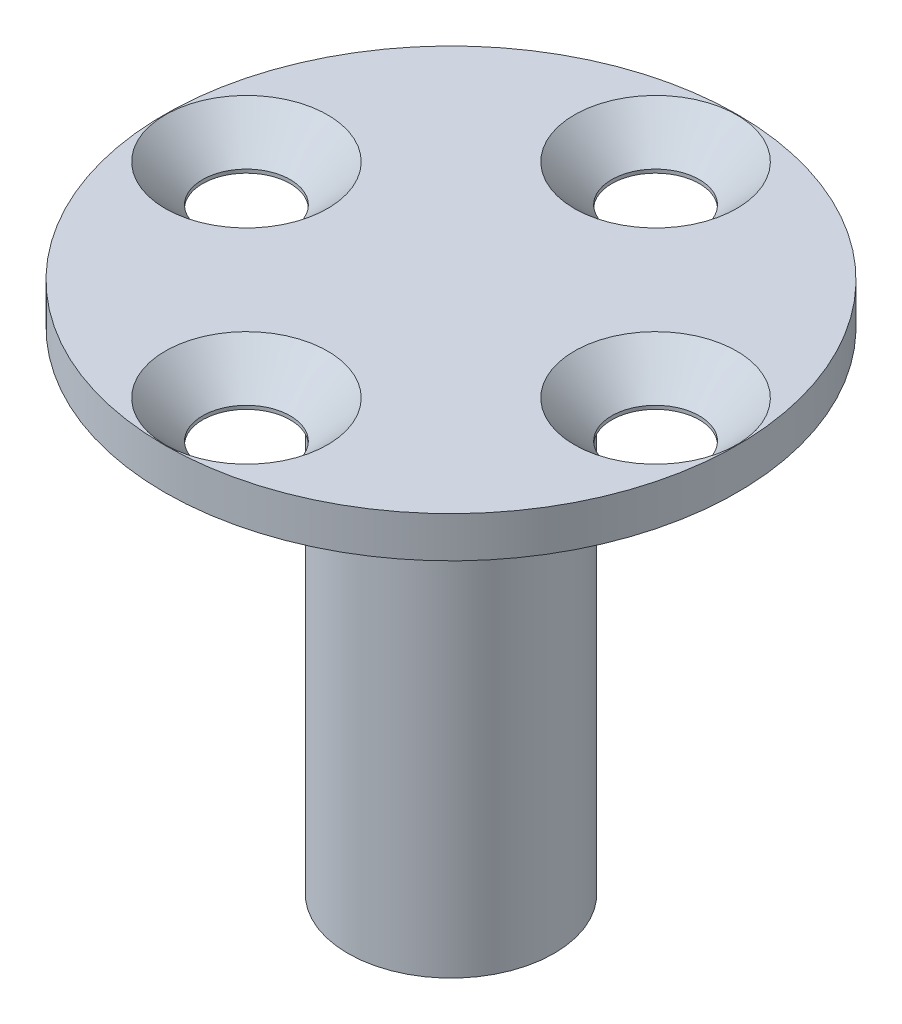
SolidWorks part; units mm, degrees
material "6061 Alloy"
ref_plane "Front" through (0, 0, 0) normal (0, 0, 1) x (1, 0, 0)
ref_plane "Top" through (0, 0, 0) normal (0, 1, 0) x (1, 0, 0)
ref_plane "Right" through (0, 0, 0) normal (1, 0, 0) x (0, 0, -1)
sketch "Sketch1" plane through (0, 0, 0) normal (0, 1, 0) x (1, 0, 0)
  circle A0 centre (0, 0) radius 4
  dimension "D1" = 8
extrude "Boss-Extrude1" add sketch "Sketch1" against normal blind 19.05
sketch "Sketch2" plane through (0, 0, 0) normal (0, 1, 0) x (1, 0, 0)
  circle A0 centre (0, 0) radius 11.1125
  dimension "D1" = 22.225
extrude "Boss-Extrude2" add sketch "Sketch2" along normal blind 3.175
sketch "Sketch10" plane through (0, 3.175, 0) normal (0, 1, 0) x (1, 0, 0)
  circle A0 centre (0, 0) radius 11.1125
  circle A1 centre (0, 0) radius 11.1125 construction
extrude "Cut-Extrude2" cut sketch "Sketch10" against normal blind 1.5875
sketch "Sketch3" plane through (0, 1.5875, 0) normal (0, 1, 0) x (1, 0, 0)
  circle A0 centre (0, 0) radius 7.9375 construction
  point P3 (7.9375, 0)
  point P4 (0, -7.9375)
  point P5 (0, 7.9375)
  point P6 (-7.9375, 0)
  dimension "D1" = 15.875
hole_wizard "CSK for M3 Flat Head Machine Screw1" positions "Sketch4" profile "Sketch6" countersink size "M3" standard "ANSI Metric" end condition up to next
sketch "Sketch4" plane through (0, 1.5875, 0) normal (0, 1, 0) x (1, 0, 0)
  point P13 (7.9375, 0)
  point P16 (0, 7.9375)
  point P19 (0, -7.9375)
  point P22 (-7.9375, 0)
sketch "Sketch6" plane through (7.9375, 1.5875, 0) normal (1, 0, 0) x (0, 0, 1)
  line L0 (0, 0) -> (0, 1.5875)
  line L1 (0, 1.5875) -> (1.7, 1.5875)
  line L2 (1.7, 1.5875) -> (1.7, 1.45)
  line L3 (1.7, 1.45) -> (3.15, 0)
  line L5 (3.15, 0) -> (0, 0)
  line L6 (-1.7, 1.45) -> (-3.15, 0) construction
  line L11 (0, -6.35) -> (0, 107.95) construction
  dimension "Thru Hole Dia." = 3.4
  dimension "Thru Hole Depth" = 1.5875
  dimension "Near C'Sink Dia." = 6.3
  dimension "Near C'Sink Angle" = 90
fillet "Fillet2" [suppressed] radius 5
